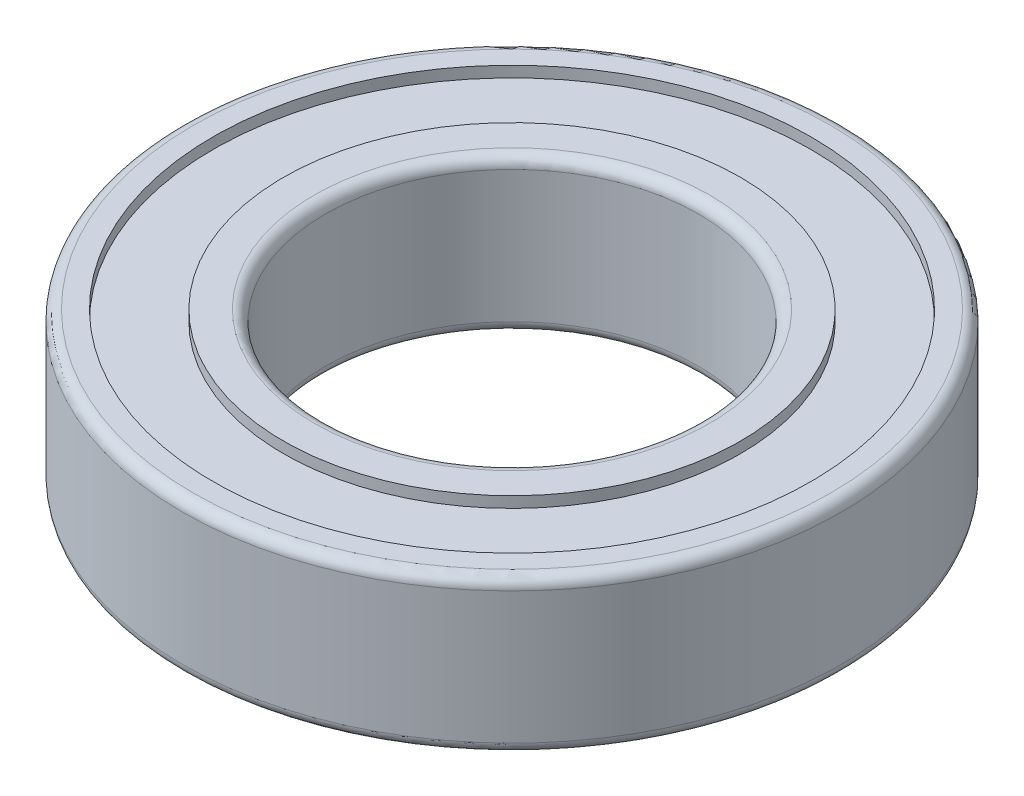
SolidWorks part; units mm, degrees
ref_plane "Ebene vorne" through (0, 0, 0) normal (0, 0, 1) x (1, 0, 0)
ref_plane "Ebene oben" through (0, 0, 0) normal (0, 1, 0) x (1, 0, 0)
ref_plane "Ebene rechts" through (0, 0, 0) normal (1, 0, 0) x (0, 0, -1)
sketch "Skizze1" plane through (0, 0, 0) normal (0, 0, 1) x (1, 0, 0)
  line L0 (0, 0) -> (0, 22.8918) construction
  line L1 (8.5, 0) -> (10.4, 0)
  line L2 (10.4, 0) -> (10.4, 0.5)
  line L3 (10.4, 0.5) -> (13.6, 0.5)
  line L4 (13.6, 0.5) -> (13.6, 0)
  line L5 (13.6, 0) -> (15, 0)
  line L6 (15, 0) -> (15, 7)
  line L7 (15, 7) -> (13.6, 7)
  line L8 (13.6, 7) -> (13.6, 6.5)
  line L9 (13.6, 6.5) -> (10.4, 6.5)
  line L10 (10.4, 6.5) -> (10.4, 7)
  line L11 (10.4, 7) -> (8.5, 7)
  line L12 (8.5, 7) -> (8.5, 0)
  dimension "D1" = 17
  dimension "D2" = 30
  dimension "D3" = 27.2
  dimension "D4" = 20.8
  dimension "D5" = 0.5
  dimension "D6" = 7
  dimension "D7" = 0.5
revolve "Rotation1" add sketch "Skizze1" angle 360 about L0
fillet "Verrundung1" radius 0.5 4 edges at (0, 0, -15) (0, 0, -8.5) (0, 7, -15) (0, 7, -8.5)
